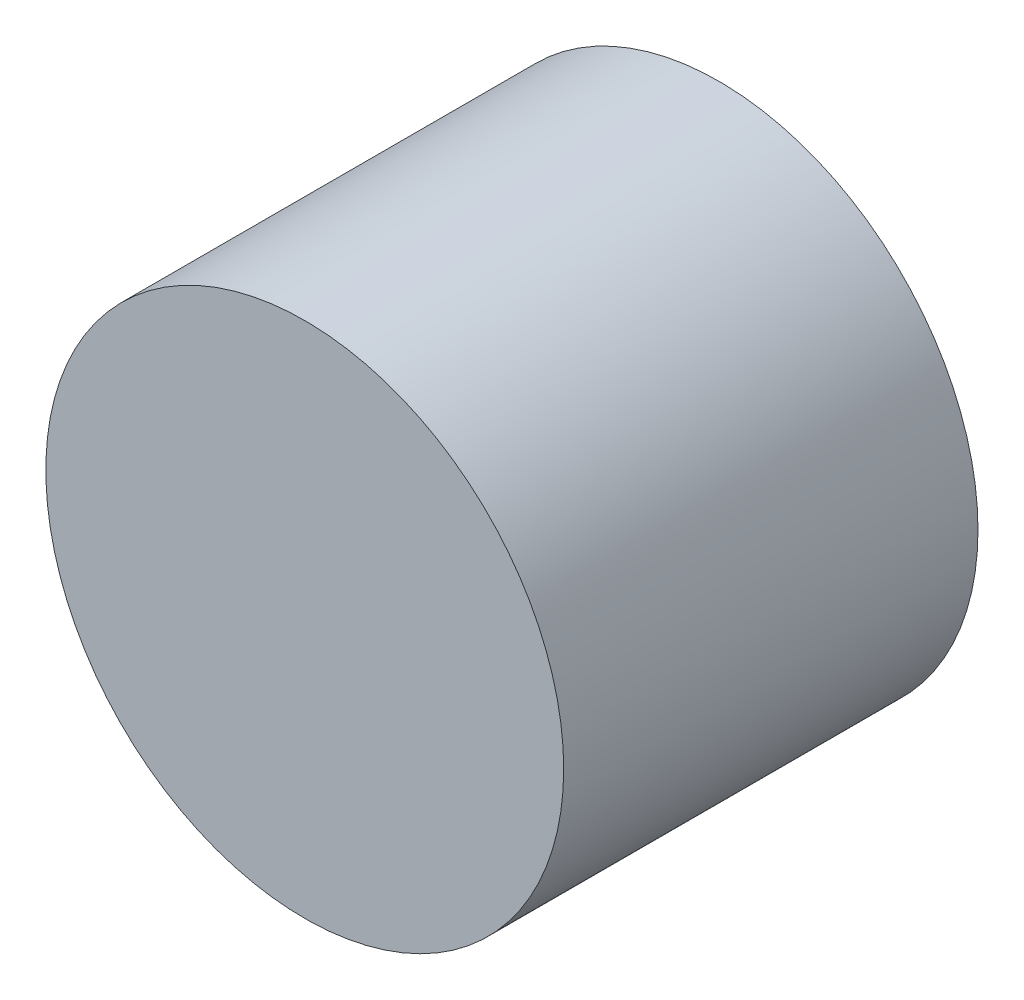
SolidWorks part; units mm, degrees
ref_plane "Front Plane" through (0, 0, 0) normal (0, 0, 1) x (1, 0, 0)
ref_plane "Top Plane" through (0, 0, 0) normal (0, 1, 0) x (1, 0, 0)
ref_plane "Right Plane" through (0, 0, 0) normal (1, 0, 0) x (0, 0, -1)
sketch "Sketch1" plane through (0, 0, 0) normal (0, 0, 1) x (1, 0, 0)
  circle A0 centre (0, 0) radius 1.5
extrude "Ball" add sketch "Sketch1" along normal blind 1
ref_plane "Plane_z1" through (0, 0, 1) normal (0, 0, 1) x (1, 0, 0)
sketch "Sketch2" plane through (0, 0, 1) normal (0, 0, 1) x (1, 0, 0)
  circle A0 centre (0, 0) radius 2.5
extrude "Sleeve" add sketch "Sketch2" along normal blind 4
fillet "Ball_round" radius 0.9 1 edges at (1.5, 0, 0)
